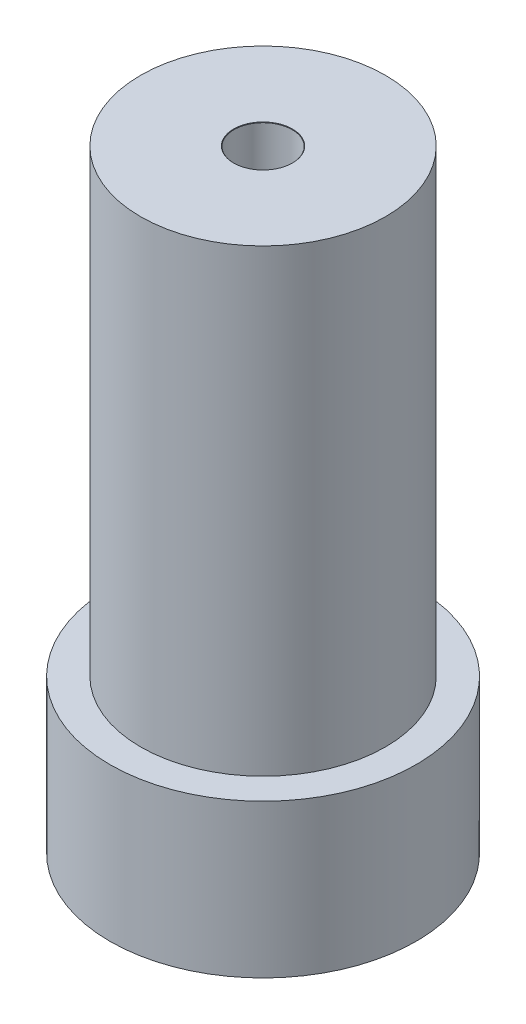
SolidWorks part; units mm, degrees
ref_plane "Front Plane" through (0, 0, 0) normal (0, 0, 1) x (1, 0, 0)
ref_plane "Top Plane" through (0, 0, 0) normal (0, 1, 0) x (1, 0, 0)
ref_plane "Right Plane" through (0, 0, 0) normal (1, 0, 0) x (0, 0, -1)
sketch "Sketch1" plane through (0, 0, 0) normal (0, 1, 0) x (1, 0, 0)
  circle A0 centre (0, 0) radius 10
  dimension "D1" = 20
extrude "Boss-Extrude1" add sketch "Sketch1" along normal blind 40
hole_wizard "Ø3.8 (3.8) Diameter Hole1" positions "Sketch2" profile "Sketch4" hole size "Ø3.8" standard "ISO"
sketch "Sketch2" plane through (0, 40, 0) normal (0, 1, 0) x (1, 0, 0)
  point P0 (0, 0)
sketch "Sketch4" plane through (0, 40, 0) normal (1, 0, 0) x (0, 0, 1)
  line L0 (0, 0) -> (0, 16.1416)
  line L1 (0, 16.1416) -> (1.9, 15)
  line L2 (1.9, 15) -> (1.9, 0.025)
  line L3 (1.9, 0.025) -> (1.925, 0)
  line L5 (1.925, 0) -> (0, 0)
  line L6 (-1.9, 0.025) -> (-1.925, 0) construction
  line L10 (0, 16.1416) -> (-1.9, 15) construction
  line L11 (0, -6.35) -> (0, 107.95) construction
  dimension "Hole Dia." = 3.8
  dimension "Hole Depth" = 15
  dimension "Near C'Sink Dia." = 3.85
  dimension "Near C'Sink Angle" = 90
  dimension "Drill Angle" = 118
sketch "Sketch5" plane through (0, 40, 0) normal (0, 1, 0) x (1, 0, 0)
  circle A0 centre (0, 0) radius 8
  circle A1 centre (0, 0) radius 13.853
  dimension "D1" = 16
extrude "Cut-Extrude1" cut sketch "Sketch5" against normal blind 30
